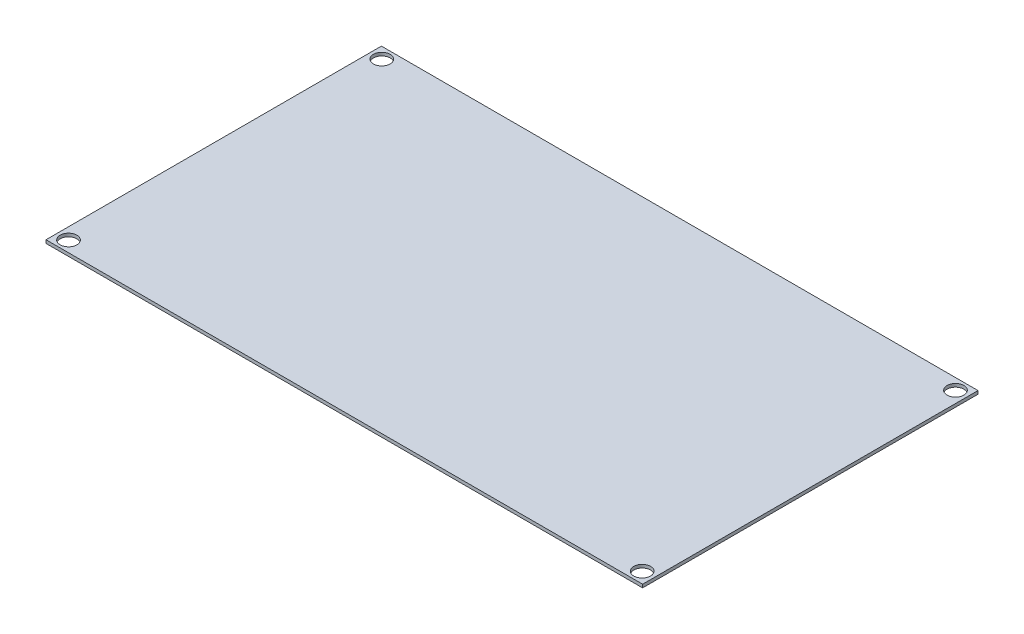
SolidWorks part; units mm, degrees
ref_plane "Front Plane" through (0, 0, 0) normal (0, 0, 1) x (1, 0, 0)
ref_plane "Top Plane" through (0, 0, 0) normal (0, 1, 0) x (1, 0, 0)
ref_plane "Right Plane" through (0, 0, 0) normal (1, 0, 0) x (0, 0, -1)
sketch "Sketch1" plane through (0, 0, 0) normal (0, 1, 0) x (1, 0, 0)
  line L0 (0, 52) -> (0, -52) construction
  line L1 (-92.5, 52) -> (92.5, 52)
  line L2 (-92.5, 52) -> (-92.5, -52)
  line L3 (-92.5, -52) -> (92.5, -52)
  line L4 (92.5, 52) -> (92.5, -52)
  line L5 (-92.5, 52) -> (92.5, -52) construction
  line L6 (-92.5, -52) -> (92.5, 52) construction
  line L7 (-92.5, 0) -> (92.5, 0) construction
  circle A0 centre (-88.94, 48.575) radius 2.6
  circle A1 centre (88.94, 48.575) radius 2.6
  circle A2 centre (88.94, -48.575) radius 2.6
  circle A3 centre (-88.94, -48.575) radius 2.6
  point P0 (0, 0)
  dimension "D3" = 5.2
  dimension "D1" = 185
  dimension "D4" = 88.94
  dimension "D5" = 48.575
extrude "Boss-Extrude1" add sketch "Sketch1" along normal blind 1
